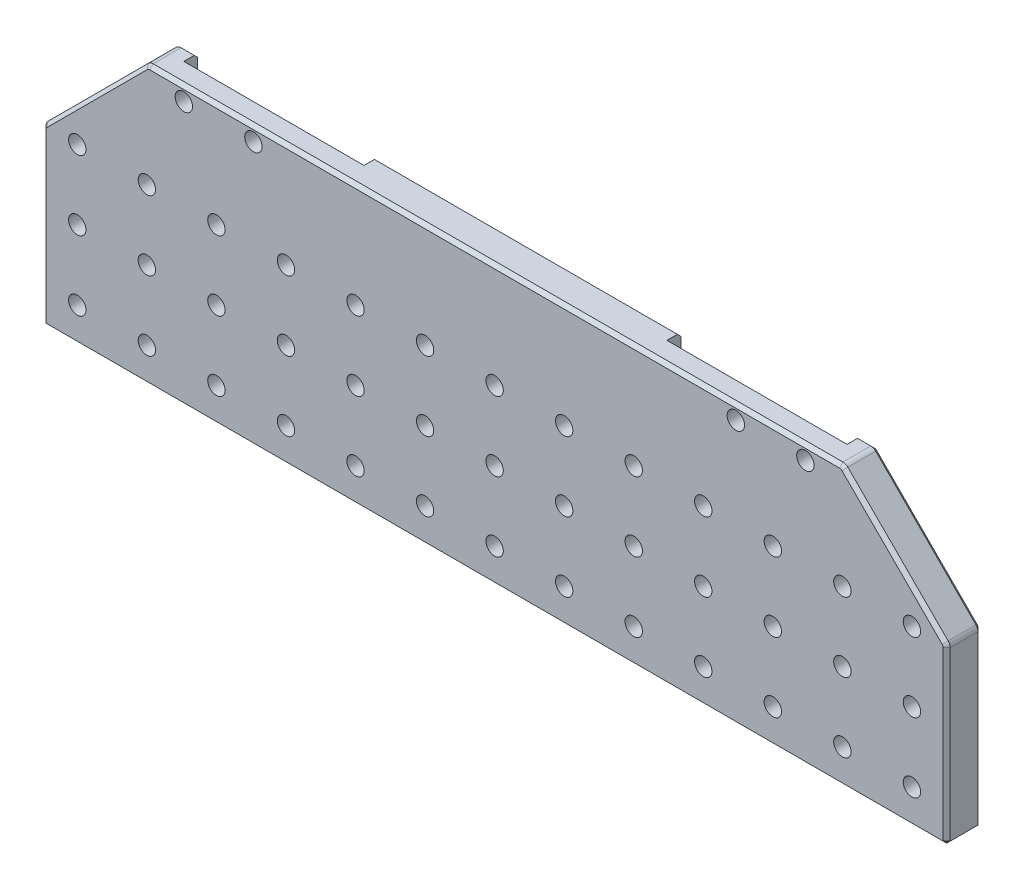
SolidWorks part; units mm, degrees
material "5052-H38"
ref_plane "Front" through (0, 0, 0) normal (0, 0, 1) x (1, 0, 0)
ref_plane "Top" through (0, 0, 0) normal (0, 1, 0) x (1, 0, 0)
ref_plane "Right" through (0, 0, 0) normal (1, 0, 0) x (0, 0, -1)
sketch "ｽｹｯﾁ2" plane through (0, 0, 0) normal (0, 0, 1) x (1, 0, 0)
  line L0 (-80.5, -17) -> (-80.5, -1.5) construction
  line L1 (-145.5, -52) -> (-15.5, -52)
  line L2 (-145.5, -52) -> (-145.5, -12)
  line L3 (-145.5, -12) -> (-15.5, -12)
  line L4 (-15.5, -52) -> (-15.5, -12)
  line L5 (-145.5, -52) -> (-15.5, -12) construction
  line L6 (-145.5, -12) -> (-15.5, -52) construction
  line L7 (-87.5, -17) -> (-73.5, -17) construction
  line L9 (-58.932, -1.5) -> (-102.068, -1.5) construction
  point P4 (-80.5, -32)
  dimension "D1" = 5
  dimension "D2" = 130
  dimension "D3" = 40
extrude "ﾎﾞｽ - 押し出し1" add sketch "ｽｹｯﾁ2" along normal blind 3 and the other way blind 2
sketch "ｽｹｯﾁ3" plane through (0, 0, -2) normal (0, 0, -1) x (-1, 0, 0)
  line L0 (128.1819, -9.5) -> (128.1819, -16.5) construction
  line L1 (32.8181, -9.5) -> (32.8181, -16.5) construction
  line L2 (128.1819, -9.5) -> (128.1819, -16.5)
  line L3 (32.8181, -9.5) -> (32.8181, -16.5)
  line L4 (49.7513, -17) -> (33.3181, -17) construction
  line L5 (33.3181, -9) -> (49.7513, -9) construction
  line L6 (49.7513, -17) -> (33.3181, -17)
  line L7 (33.3181, -9) -> (49.7513, -9)
  line L8 (107.8849, -16.5) -> (107.8849, -9.5)
  line L9 (102.2786, -16.5) -> (107.8849, -16.5)
  line L10 (102.2786, -9.5) -> (102.2786, -16.5)
  line L11 (107.8849, -9.5) -> (102.2786, -9.5)
  line L12 (107.8849, -16.5) -> (107.8849, -9.5)
  line L13 (102.2786, -16.5) -> (107.8849, -16.5)
  line L14 (102.2786, -9.5) -> (102.2786, -16.5)
  line L15 (107.8849, -9.5) -> (102.2786, -9.5)
  line L16 (58.7214, -16.5) -> (58.7214, -9.5)
  line L17 (53.1151, -16.5) -> (58.7214, -16.5)
  line L18 (53.1151, -9.5) -> (53.1151, -16.5)
  line L19 (58.7214, -9.5) -> (53.1151, -9.5)
  line L20 (58.7214, -16.5) -> (58.7214, -9.5)
  line L21 (53.1151, -16.5) -> (58.7214, -16.5)
  line L22 (53.1151, -9.5) -> (53.1151, -16.5)
  line L23 (58.7214, -9.5) -> (53.1151, -9.5)
  line L24 (111.2487, -9) -> (127.6819, -9) construction
  line L25 (127.6819, -17) -> (111.2487, -17) construction
  line L26 (111.2487, -9) -> (127.6819, -9)
  line L27 (127.6819, -17) -> (111.2487, -17)
  circle A0 centre (58, -33.2) radius 1.25 construction
  circle A1 centre (103, -33.2) radius 1.25 construction
  circle A2 centre (125.1819, -14) radius 1.6 construction
  circle A3 centre (35.8181, -14) radius 1.6 construction
  circle A4 centre (125.1819, -14) radius 1.6
  circle A5 centre (35.8181, -14) radius 1.6
  circle A6 centre (115.1819, -14) radius 1.6 construction
  circle A7 centre (45.8181, -14) radius 1.6 construction
  circle A8 centre (115.1819, -14) radius 1.6
  circle A9 centre (45.8181, -14) radius 1.6
  dimension "D1" = 2.5
  dimension "D2" = 0
  dimension "D3" = 0
sketch "ｽｹｯﾁ4" plane through (0, 0, -2) normal (0, 0, 1) x (1, 0, 0)
  line L0 (-15.5, -12) -> (-145.5, -12) construction
  line L1 (-128.1819, -17) -> (-102.2786, -17)
  line L2 (-128.1819, -17) -> (-128.1819, -12)
  line L3 (-128.1819, -12) -> (-102.2786, -12)
  line L4 (-102.2786, -17) -> (-102.2786, -12)
  line L5 (-128.1819, -17) -> (-102.2786, -12) construction
  line L6 (-128.1819, -12) -> (-102.2786, -17) construction
  line L7 (-128.1819, -9.5) -> (-128.1819, -16.5) construction
  line L8 (-127.6819, -17) -> (-111.2487, -17) construction
  line L9 (-102.2786, -9.5) -> (-102.2786, -16.5) construction
  line L10 (-80.5, -12) -> (-80.5, -52) construction
  line L11 (-145.5, -52) -> (-15.5, -52) construction
  line L12 (-32.8181, -12) -> (-58.7214, -17) construction
  line L13 (-32.8181, -17) -> (-58.7214, -12) construction
  line L14 (-58.7214, -17) -> (-58.7214, -12)
  line L15 (-32.8181, -12) -> (-58.7214, -12)
  line L16 (-32.8181, -17) -> (-32.8181, -12)
  line L17 (-32.8181, -17) -> (-58.7214, -17)
  point P4 (-115.2302, -14.5)
  point P21 (-45.7698, -14.5)
sketch "ｽｹｯﾁ6" plane through (0, 0, -2) normal (0, 0, -1) x (-1, 0, 0)
  line L4 (102.2786, -17) -> (128.1819, -17)
  line L5 (102.2786, -12) -> (102.2786, -17)
  line L6 (128.1819, -12) -> (102.2786, -12)
  line L7 (128.1819, -17) -> (128.1819, -12)
  line L8 (102.2786, -17) -> (128.1819, -17)
  line L9 (102.2786, -12) -> (102.2786, -17)
  line L10 (128.1819, -12) -> (102.2786, -12)
  line L11 (128.1819, -17) -> (128.1819, -12)
  line L12 (58.7214, -17) -> (58.7214, -12)
  line L13 (58.7214, -12) -> (32.8181, -12)
  line L14 (32.8181, -12) -> (32.8181, -17)
  line L15 (32.8181, -17) -> (58.7214, -17)
  line L16 (58.7214, -17) -> (58.7214, -12)
  line L17 (58.7214, -12) -> (32.8181, -12)
  line L18 (32.8181, -12) -> (32.8181, -17)
  line L19 (32.8181, -17) -> (58.7214, -17)
  dimension "D1" = 0
  dimension "D2" = 0
extrude "ｶｯﾄ - 押し出し6" cut sketch "ｽｹｯﾁ6" against normal blind 2
sketch "ｽｹｯﾁ7" plane through (0, 0, -2) normal (0, 0, -1) x (-1, 0, 0)
  circle A0 centre (33.3181, -17) radius 2.5
  circle A1 centre (128.1819, -17) radius 2.5
  circle A2 centre (102.2786, -17) radius 2.5
  circle A3 centre (58.7214, -17) radius 2.5
  dimension "D1" = 5
extrude "ｶｯﾄ - 押し出し7" cut sketch "ｽｹｯﾁ7" against normal blind 2
chamfer "面取り1" distance 15 angle 45 2 edges at (-145.5, -12, 0.5) (-15.5, -12, 0.5)
hole_wizard "M3x0.5 ねじ穴1" positions "ｽｹｯﾁ8" profile "ｽｹｯﾁ9" tap size "M3x0.5" standard "JIS"
sketch "ｽｹｯﾁ8" plane through (0, 0, 0) normal (0, 0, -1) x (-1, 0, 0)
  point P0 (35.8181, -14)
  point P3 (125.1819, -14)
  point P7 (45.8181, -14)
  point P10 (115.1819, -14)
sketch "ｽｹｯﾁ9" plane through (-35.8181, -14, 0) normal (1, 0, 0) x (0, 1, 0)
  line L0 (0, 0) -> (0, 9.2511)
  line L1 (0, 9.2511) -> (1.25, 8.5)
  line L2 (1.25, 8.5) -> (1.25, 0)
  line L5 (1.25, 0) -> (0, 0)
  line L10 (0, 9.2511) -> (-1.25, 8.5) construction
  line L11 (0, -6.35) -> (0, 107.95) construction
  dimension "ねじ下穴ﾄﾞﾘﾙ直径" = 2.5
  dimension "ねじ下穴ﾄﾞﾘﾙの深さ" = 8.5
  dimension "ﾄﾞﾘﾙ角度" = 118
cosmetic thread "穴のねじ山1" parameters "D1"=2, "D2"=3
cosmetic thread "穴のねじ山2" parameters "D1"=2, "D2"=3
cosmetic thread "穴のねじ山3" parameters "D1"=2, "D2"=3
cosmetic thread "穴のねじ山4" parameters "D1"=2, "D2"=3
fillet "ﾌｨﾚｯﾄ1" radius 1 4 edges at (-145.5, -27, 0.5) (-130.5, -12, 0.5) (-30.5, -12, 0.5) (-15.5, -27, 0.5)
hole_wizard "M3x0.5 ねじ穴2" positions "ｽｹｯﾁ10" profile "ｽｹｯﾁ11" tap size "M3x0.5" standard "JIS"
sketch "ｽｹｯﾁ10" plane through (0, 0, -2) normal (0, 0, -1) x (-1, 0, 0)
  line L0 (80.5, -12) -> (80.5, -52) construction
  line L1 (145.5, -52) -> (15.5, -52) construction
  point P0 (80.5, -47)
  dimension "D1" = 5
sketch "ｽｹｯﾁ11" plane through (-80.5, -47, -2) normal (1, 0, 0) x (0, 1, 0)
  line L0 (0, 0) -> (0, 9.2511)
  line L1 (0, 9.2511) -> (1.25, 8.5)
  line L2 (1.25, 8.5) -> (1.25, 0)
  line L5 (1.25, 0) -> (0, 0)
  line L10 (0, 9.2511) -> (-1.25, 8.5) construction
  line L11 (0, -6.35) -> (0, 107.95) construction
  dimension "ねじ下穴ﾄﾞﾘﾙ直径" = 2.5
  dimension "ねじ下穴ﾄﾞﾘﾙの深さ" = 8.5
  dimension "ﾄﾞﾘﾙ角度" = 118
cosmetic thread "穴のねじ山5" parameters "D1"=5, "D2"=3
pattern_linear "直線ﾊﾟﾀｰﾝ1" count 7 spacing 10 along (1, 0, 0) count 3 spacing 10 along (0, 1, 0) of "M3x0.5 ねじ穴2"
pattern_linear "直線ﾊﾟﾀｰﾝ2" count 7 spacing 10 along (-1, 0, 0) count 3 spacing 10 along (0, 1, 0) of "M3x0.5 ねじ穴2"
chamfer "面取り2" distance 0.5 angle 45 24 edges at (-80.5, -12, -2) (-80.5, -12, 3) (-129.1338, -12, -2) (-31.8662, -12, -2) (-30.5315, -12.0761, 3) (-130.4685, -12.0761, 3) (-130.4685, -12.0761, -2) (-30.5315, -12.0761, -2) (-23, -19.5, 3) (-138, -19.5, 3) (-138, -19.5, -2) (-23, -19.5, -2) (-15.5761, -27.0315, 3) (-145.4239, -27.0315, 3) (-145.4239, -27.0315, -2) (-15.5761, -27.0315, -2) (-15.5, -39.7071, 3) (-145.5, -39.7071, 3) (-80.5, -52, 3) (-145.5, -52, 0.5) (-15.5, -52, 0.5) (-145.5, -39.7071, -2) (-80.5, -52, -2) (-15.5, -39.7071, -2)
